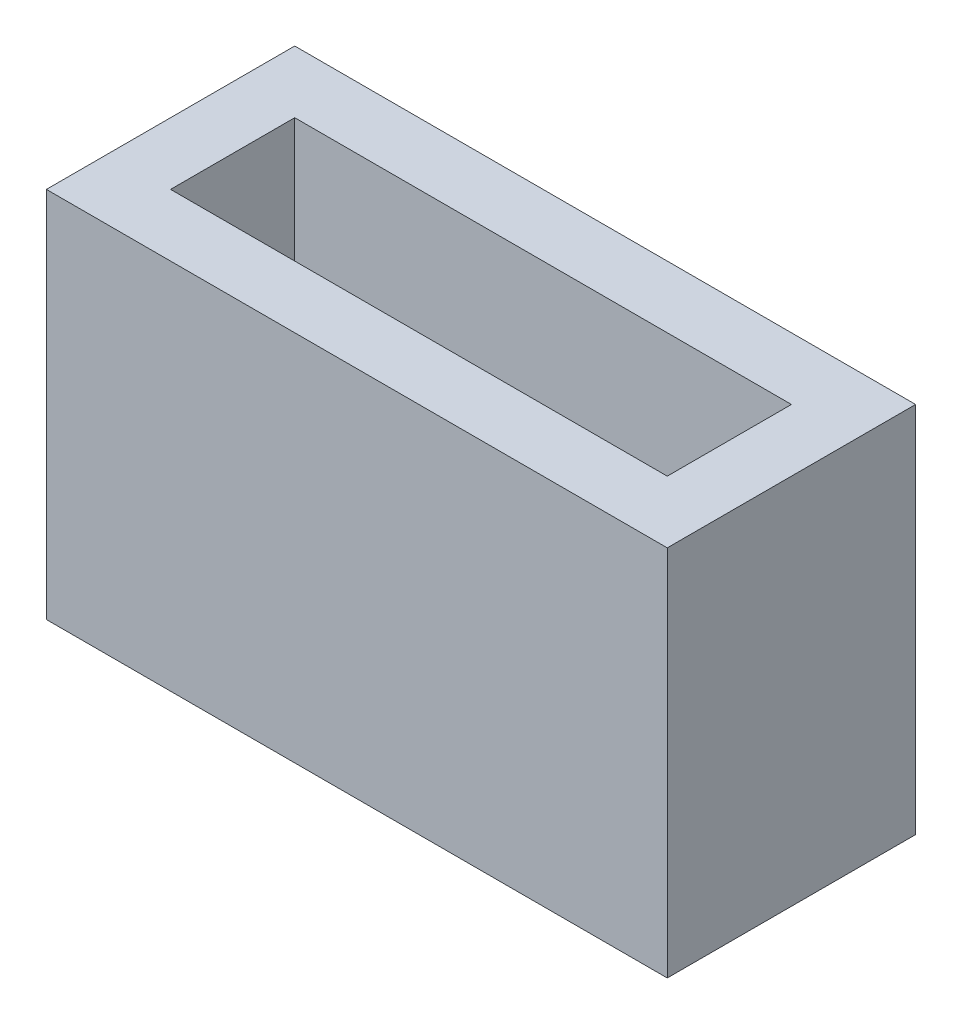
SolidWorks part; units mm, degrees
ref_plane "前视基准面" through (0, 0, 0) normal (0, 0, 1) x (1, 0, 0)
ref_plane "上视基准面" through (0, 0, 0) normal (0, 1, 0) x (1, 0, 0)
ref_plane "右视基准面" through (0, 0, 0) normal (1, 0, 0) x (0, 0, -1)
sketch "草图2" plane through (0, 0, 0) normal (0, 1, 0) x (1, 0, 0)
  line L1 (-25, 10) -> (25, 10)
  line L2 (-25, 10) -> (-25, -10)
  line L3 (-25, -10) -> (25, -10)
  line L4 (25, 10) -> (25, -10)
  line L5 (-25, 10) -> (25, -10) construction
  line L6 (-25, -10) -> (25, 10) construction
  line L7 (20, -5) -> (-20, -5)
  line L8 (20, -5) -> (20, 5)
  line L9 (20, 5) -> (-20, 5)
  line L10 (-20, -5) -> (-20, 5)
  line L11 (20, -5) -> (-20, 5) construction
  line L12 (20, 5) -> (-20, -5) construction
  point P0 (0, 0)
  point P6 (0, 0)
  dimension "D1" = 50
  dimension "D2" = 40
  dimension "D3" = 20
  dimension "D4" = 10
extrude "凸台-拉伸1" add sketch "草图2" along normal blind 30
sketch "草图3" plane through (0, 0, -10) normal (0, 0, -1) x (-1, 0, 0)
  circle A0 centre (0, 15) radius 5
extrude "切除-拉伸1" cut sketch "草图3" against normal blind 5
